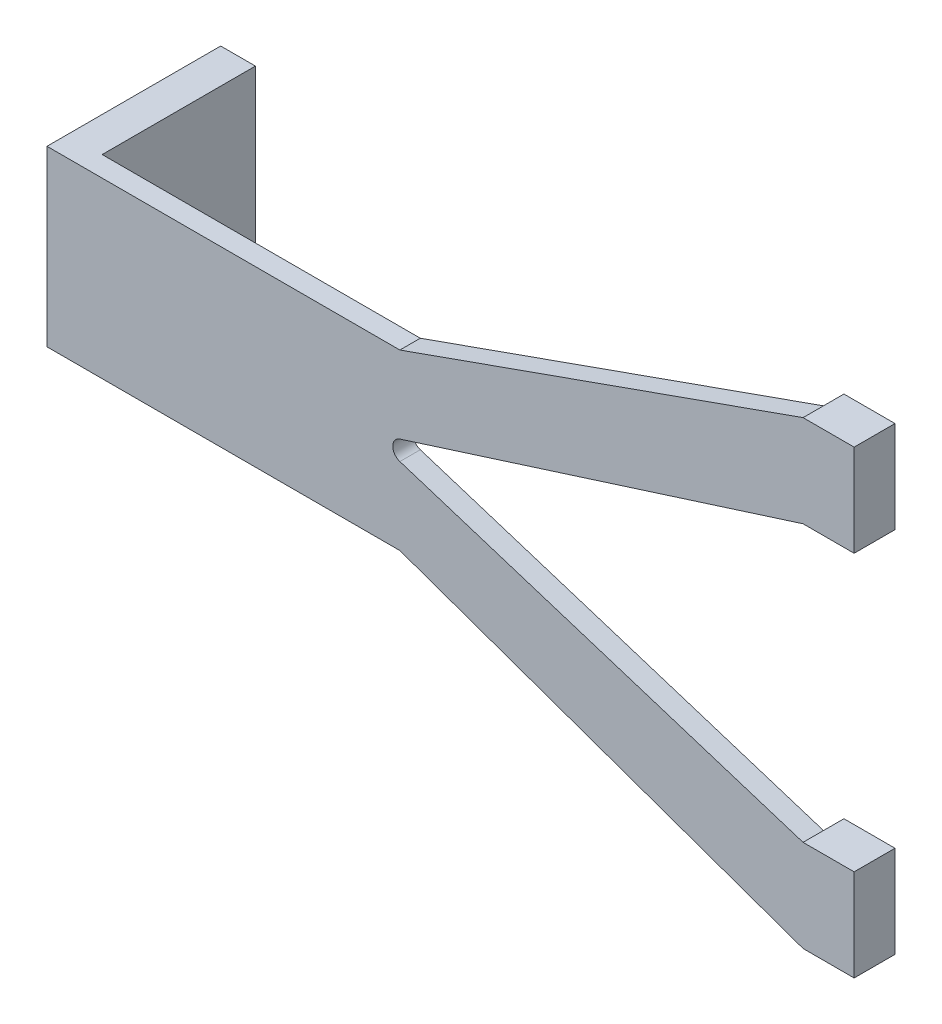
SolidWorks part; units mm, degrees
ref_plane "정면" through (0, 0, 0) normal (0, 0, 1) x (1, 0, 0)
ref_plane "윗면" through (0, 0, 0) normal (0, 1, 0) x (1, 0, 0)
ref_plane "우측면" through (0, 0, 0) normal (1, 0, 0) x (0, 0, -1)
sketch "스케치1" plane through (0, 0, 0) normal (0, 0, 1) x (1, 0, 0)
  line L0 (30.6604, 8.5) -> (70.1215, 22.5)
  line L2 (-3.8785, -8.5) -> (-3.8785, 8.5)
  line L3 (-3.8785, 8.5) -> (30.6604, 8.5)
  line L5 (70.1215, 22.5) -> (70.1215, 13.5) construction
  line L6 (70.1215, 13.5) -> (30.6604, 0.953)
  line L7 (55, 0) -> (-55, 0) construction
  line L8 (70.1215, -13.5) -> (30.6604, -0.953)
  line L9 (70.1215, -22.5) -> (70.1215, -13.5) construction
  line L10 (-3.8785, -8.5) -> (30.6604, -8.5)
  line L11 (30.6604, -8.5) -> (70.1215, -22.5)
  line L12 (70.1215, 13.5) -> (75.1215, 13.5)
  line L13 (70.1215, -22.5) -> (75.1215, -22.5)
  line L14 (70.1215, -22.5) -> (70.1215, -13.5) construction
  line L15 (70.1215, -13.5) -> (75.1215, -13.5)
  line L16 (75.1215, -22.5) -> (75.1215, -13.5)
  line L17 (75.1215, 22.5) -> (75.1215, 13.5)
  line L18 (70.1215, 22.5) -> (75.1215, 22.5)
  arc A0 (30.6604, 0.953) -> (30.6604, -0.953) centre (30.9634, 0) ccw
  point P12 (-3.8785, 0)
  dimension "D3" = 1
  dimension "D1" = 17
  dimension "D2" = 9
  dimension "D4" = 74
  dimension "D5" = 45
  dimension "D6" = 5
extrude "보스-돌출1" add sketch "스케치1" along normal blind 2
sketch "스케치3" plane through (0, 0, 0) normal (0, 0, -1) x (-1, 0, 0)
  line L0 (-30.6604, 8.5) -> (3.8785, 8.5) construction
  line L1 (3.8785, -8.5) -> (0.4785, -8.5)
  line L2 (3.8785, -8.5) -> (3.8785, 8.5)
  line L3 (3.8785, 8.5) -> (0.4785, 8.5)
  line L4 (0.4785, -8.5) -> (0.4785, 8.5)
  dimension "D1" = 3.4
extrude "보스-돌출2" add sketch "스케치3" along normal blind 15
sketch "스케치6" plane through (0, 0, 0) normal (0, 0, -1) x (-1, 0, 0)
  line L0 (-70.1215, -22.5) -> (-70.1215, -13.5)
  line L1 (55, 0) -> (-55, 0) construction
  line L3 (-75.1215, 22.5) -> (-70.1215, 22.5)
  line L5 (-75.1215, 13.5) -> (-75.1215, 22.5)
  line L6 (-70.1215, 13.5) -> (-75.1215, 13.5)
  line L7 (-70.1215, 22.5) -> (-70.1215, 13.5)
  line L13 (0.4785, -8.5) -> (0.4785, 8.5)
  line L14 (0.4785, 8.5) -> (-30.6604, 8.5)
  line L15 (-30.6604, 8.5) -> (-70.1215, 22.5)
  line L16 (-70.1215, 22.5) -> (-75.1215, 22.5)
  line L17 (-75.1215, 22.5) -> (-75.1215, 13.5)
  line L18 (-75.1215, 13.5) -> (-70.1215, 13.5)
  line L19 (-70.1215, 13.5) -> (-30.6604, 0.953)
  line L20 (-30.6604, -0.953) -> (-70.1215, -13.5)
  line L21 (-70.1215, -13.5) -> (-75.1215, -13.5)
  line L22 (-75.1215, -13.5) -> (-75.1215, -22.5)
  line L23 (-75.1215, -22.5) -> (-70.1215, -22.5)
  line L24 (-70.1215, -22.5) -> (-30.6604, -8.5)
  line L25 (-30.6604, -8.5) -> (0.4785, -8.5)
  line L34 (-70.1215, -13.5) -> (-75.1215, -13.5)
  line L35 (-75.1215, -13.5) -> (-75.1215, -22.5)
  line L36 (-75.1215, -22.5) -> (-70.1215, -22.5)
  arc A1 (-30.6604, -0.953) -> (-30.6604, 0.953) centre (-30.9634, 0) ccw
  point P8 (0, 0)
  point P10 (0, 0)
  line M19 (-70.1215, 22.5) -> (-75.1215, 22.5)
  line M20 (-75.1215, 22.5) -> (-75.1215, 13.5)
  line M21 (-75.1215, 13.5) -> (-70.1215, 13.5)
  line M25 (-70.1215, -13.5) -> (-75.1215, -13.5)
  line M26 (-75.1215, -13.5) -> (-75.1215, -22.5)
  line M27 (-75.1215, -22.5) -> (-70.1215, -22.5)
  dimension "D1" = 0
extrude "보스-돌출4" add sketch "스케치6" along normal blind 2 contours L7 M19 M20 M21 | L0 M27 M25 M26
